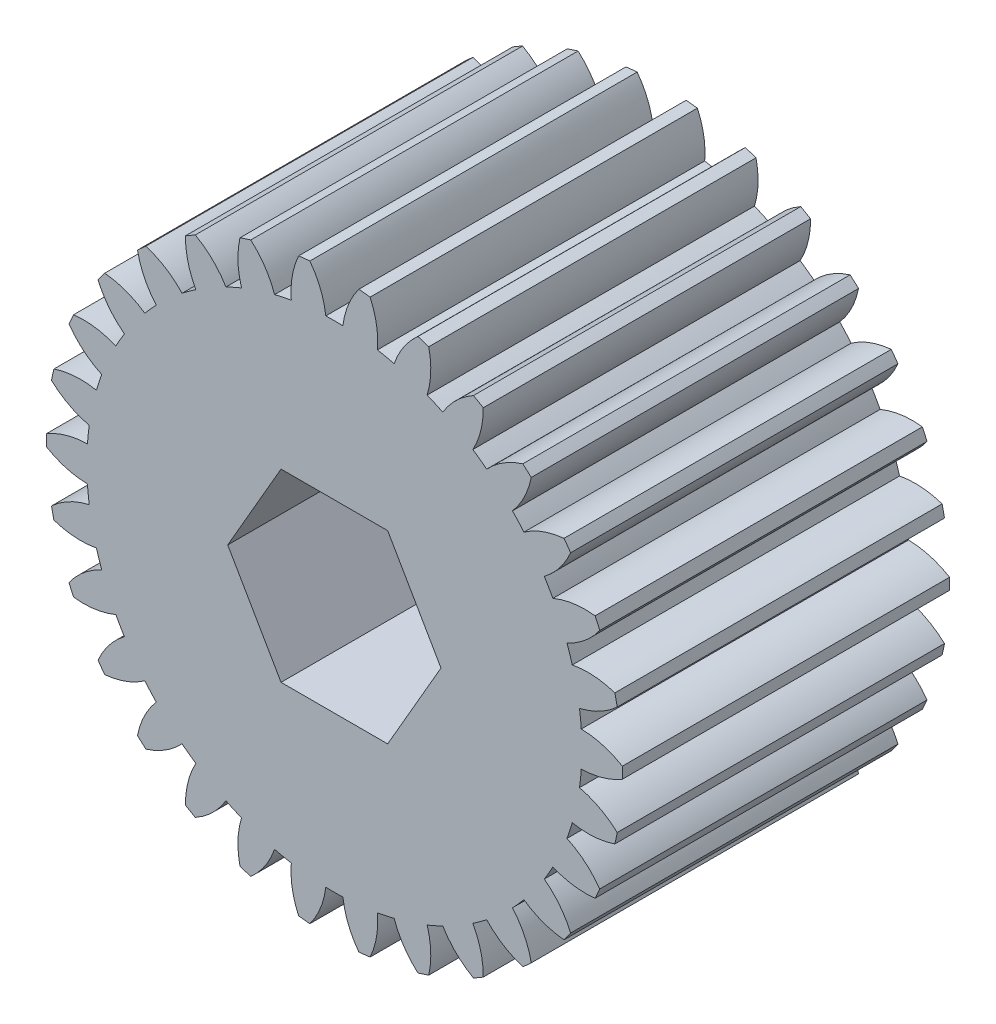
SolidWorks part; units mm, degrees
ref_plane "Front" through (0, 0, 0) normal (0, 0, 1) x (1, 0, 0)
ref_plane "Top" through (0, 0, 0) normal (0, 1, 0) x (1, 0, 0)
ref_plane "Right" through (0, 0, 0) normal (1, 0, 0) x (0, 0, -1)
sketch "Эскиз1" plane through (0, 0, 0) normal (0, 0, 1) x (1, 0, 0)
  circle A0 centre (0, 0) radius 10.5875 construction
  circle A1 centre (0, 0) radius 11.5 construction
  circle A2 centre (0, 0) radius 12.32
  circle A3 centre (0, 0) radius 10.805 construction
  dimension "D1" = 21.175
  dimension "D2" = 23
  dimension "D3" = 24.64
  dimension "D4" = 21.61
extrude "Бобышка-Вытянуть1" add sketch "Эскиз1" along normal mid plane 14
sketch "Эскиз2" plane through (0, 0, 7) normal (0, 0, 1) x (1, 0, 0)
  line L0 (-0.9448, 15.1928) -> (0, 0) construction
  line L1 (-0.7321, 11.7723) -> (-4.9391, 9.6101) construction
  line L2 (-0.6, 11.4843) -> (0.6, 11.4843) construction
  line L3 (0, 0) -> (0, 12.32) construction
  circle A0 centre (0, 0) radius 12.32 construction
  circle A1 centre (0, 0) radius 10.805 construction
  arc A2 (-1.4587, 12.7367) -> (-0.3658, 10.5812) centre (-3.8896, 10.1495) cw
  circle A3 centre (0, 0) radius 10.5875 construction
  circle A4 centre (0, 0) radius 11.5 construction
  arc A5 (1.4587, 12.7367) -> (0.3658, 10.5812) centre (3.8896, 10.1495) ccw
  arc A6 (-0.3658, 10.5812) -> (0.3658, 10.5812) centre (0, 0) cw
  circle A8 centre (0, 0) radius 12.82
  arc A9 (1.4587, 12.7367) -> (-1.4587, 12.7367) centre (0, 0) ccw
  point P3 (-0.7321, 11.7723)
  dimension "D1" = 0.525
  dimension "D2" = 1.2
  dimension "D3" = 4.7301
  dimension "D4" = 1.18
  dimension "D5" = 0.5
sketch "Эскиз4" plane through (0, 0, 0) normal (0, 1, 0) x (1, 0, 0)
  line L0 (0, 7) -> (0, -7)
  line L1 (12.32, 7) -> (-12.32, 7) construction
  line L3 (-12.32, -7) -> (12.32, -7) construction
  line L4 (0, -50) -> (0, 50) construction
  dimension "D1" = 0
curve "Кривая1"
sketch "Эскиз5" plane through (0, 0, -7) normal (0, 0, 1) x (1, 0, 0)
  line L0 (-0.9448, 15.1928) -> (0, 0) construction
  line L1 (-0.7321, 11.7723) -> (-4.9391, 9.6101) construction
  line L2 (-0.6, 11.4843) -> (0.6, 11.4843) construction
  line L3 (0, 0) -> (0, 12.32) construction
  arc A2 (-1.4587, 12.7367) -> (-0.3658, 10.5812) centre (-3.8896, 10.1495) cw
  arc A5 (1.4587, 12.7367) -> (0.3658, 10.5812) centre (3.8896, 10.1495) ccw
  arc A6 (-0.3658, 10.5812) -> (0.3658, 10.5812) centre (0, 0) cw
  arc A9 (1.4587, 12.7367) -> (-1.4587, 12.7367) centre (0, 0) ccw
  point P3 (-0.7321, 11.7723)
loft "Вырез-По сечениям1" cut profiles "Эскиз5", "Эскиз2"
pattern_circular "Круговой массив1" count 30 over 360 about axis through (0, 0, 0) along (0, 0, 1) of "Вырез-По сечениям1"
sketch "Эскиз6" plane through (0, 0, 7) normal (0, 0, 1) x (1, 0, 0)
  line L1 (-2.2805, 3.95) -> (-4.5611, 0)
  line L2 (-4.5611, 0) -> (-2.2805, -3.95)
  line L3 (-2.2805, -3.95) -> (2.2805, -3.95)
  line L4 (2.2805, -3.95) -> (4.5611, 0)
  line L5 (4.5611, 0) -> (2.2805, 3.95)
  line L6 (2.2805, 3.95) -> (-2.2805, 3.95)
  circle A0 centre (0, 0) radius 3.95 construction
  dimension "D1" = 7.9
extrude "Вырез-Вытянуть1" cut sketch "Эскиз6" against normal through all
